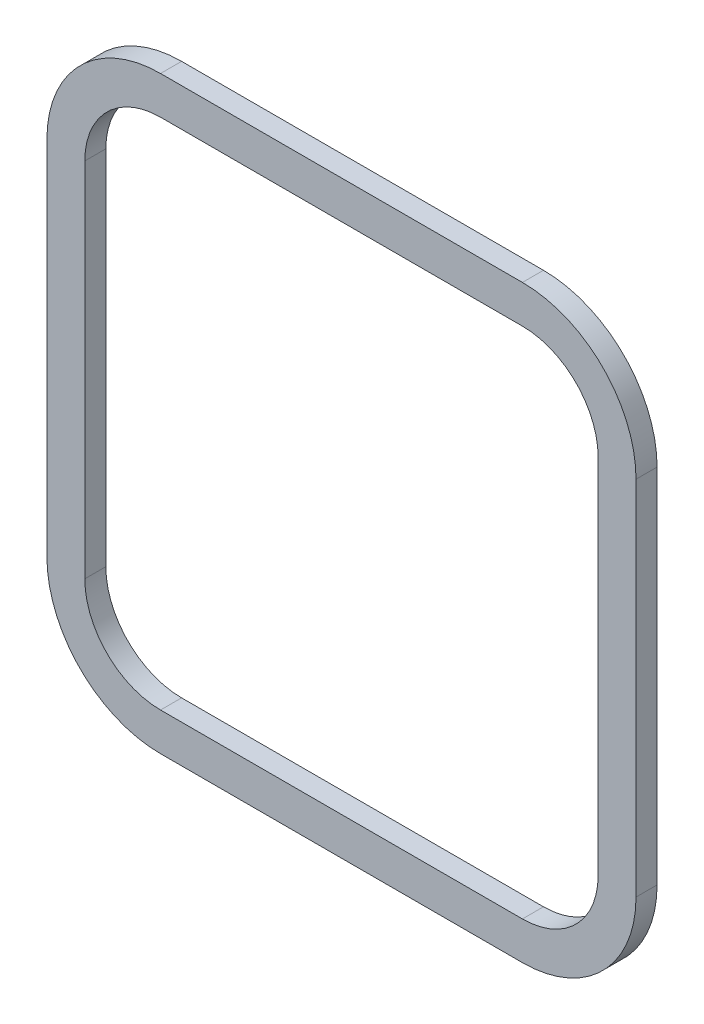
SolidWorks part; units mm, degrees
material "普通碳钢"
ref_plane "前视基准面" through (0, 0, 0) normal (0, 0, 1) x (1, 0, 0)
ref_plane "上视基准面" through (0, 0, 0) normal (0, 1, 0) x (1, 0, 0)
ref_plane "右视基准面" through (0, 0, 0) normal (1, 0, 0) x (0, 0, -1)
sketch "草图1" plane through (0, 0, 0) normal (0, 0, 1) x (1, 0, 0)
  line L0 (0, 0) -> (15.3811, 0) construction
  line L1 (-140, 140) -> (140, 140)
  line L2 (-140, 140) -> (-140, -140)
  line L3 (-140, -140) -> (140, -140)
  line L4 (140, 140) -> (140, -140)
  line L5 (-122, 122) -> (122, 122)
  line L6 (-122, 122) -> (-122, -122)
  line L7 (-122, -122) -> (122, -122)
  line L8 (122, 122) -> (122, -122)
  line L9 (0, 17.4137) -> (0, 37.0891) construction
  point P10 (0, 0)
  dimension "D1" = 280
  dimension "D2" = 18
extrude "凸台-拉伸1" add sketch "草图1" along normal blind 10
fillet "圆角1" radius 36 4 edges at (-122, -122, 5) (-122, 122, 5) (122, 122, 5) (122, -122, 5)
fillet "圆角2" radius 54 4 edges at (-140, -140, 5) (140, -140, 5) (-140, 140, 5) (140, 140, 5)
